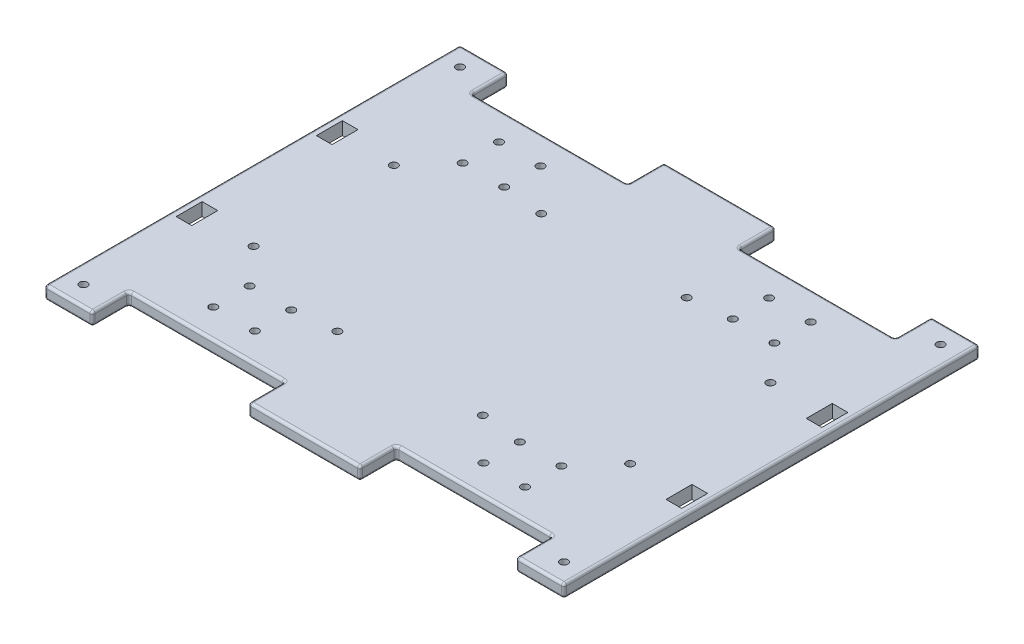
SolidWorks part; units mm, degrees
ref_plane "Front Plane" through (0, 0, 0) normal (0, 0, 1) x (1, 0, 0)
ref_plane "Top Plane" through (0, 0, 0) normal (0, 1, 0) x (1, 0, 0)
ref_plane "Right Plane" through (0, 0, 0) normal (1, 0, 0) x (0, 0, -1)
sketch "Sketch2" plane through (0, 0, 0) normal (0, 1, 0) x (1, 0, 0)
  line L1 (-100, -80) -> (100, -80)
  line L2 (-100, -80) -> (-100, 80)
  line L3 (-100, 80) -> (100, 80)
  line L4 (100, -80) -> (100, 80)
  line L5 (-100, -80) -> (100, 80) construction
  line L6 (-100, 80) -> (100, -80) construction
  point P0 (0, 0)
  dimension "D1" = 200
  dimension "D2" = 160
extrude "Boss-Extrude1" add sketch "Sketch2" along normal blind 5
sketch "Sketch3" plane through (0, 5, 0) normal (0, 1, 0) x (1, 0, 0)
  line L0 (100, -80) -> (100, 80) construction
  line L1 (100, 80) -> (-100, 80) construction
  circle A0 centre (92.5, 72.5) radius 1.5
  dimension "D1" = 3
  dimension "D3" = 7.5
  dimension "D2" = 7.5
extrude "Cut-Extrude1" cut sketch "Sketch3" against normal through all
mirror "Mirror1" about plane through (0, 0, 0) normal (1, 0, 0) of "Cut-Extrude1"
mirror "Mirror2" about plane through (0, 0, 0) normal (0, 0, 1) of "Mirror1", "Cut-Extrude1"
sketch "Sketch4" plane through (0, 5, 0) normal (0, 1, 0) x (1, 0, 0)
  line L0 (-100, 80) -> (-100, -80) construction
  line L1 (-52, -65.6362) -> (-52, -30.3638) construction
  line L2 (-36.7421, -48) -> (-67.2579, -48) construction
  line L3 (-100, -80) -> (100, -80) construction
  circle A0 centre (-60, -55) radius 1.5
  circle A1 centre (-60, -41) radius 1.5
  circle A2 centre (-44, -55) radius 1.5
  circle A3 centre (-44, -41) radius 1.5
  point P11 (-52, -48)
  dimension "D1" = 3
  dimension "D2" = 40
  dimension "D3" = 25
  dimension "D6" = 16
  dimension "D7" = 14
extrude "Cut-Extrude2" cut sketch "Sketch4" against normal through all
mirror "Mirror3" about plane through (0, 0, 0) normal (1, 0, 0) of "Cut-Extrude2"
mirror "Mirror4" about plane through (0, 0, 0) normal (0, 0, 1) of "Mirror3", "Cut-Extrude2"
sketch "Sketch6" plane through (0, 5, 0) normal (0, 1, 0) x (1, 0, 0)
  line L0 (-21.5, -80) -> (-21.5, -66)
  line L1 (-51.5, -36) -> (-51.5, -89.4353) construction
  line L2 (-81.5, -80) -> (-81.5, -66)
  line L3 (-21.5, -66) -> (-81.5, -66)
  line L7 (-100, -80) -> (100, -80) construction
  circle A0 centre (-44, -41) radius 1.5 construction
  point P8 (-71.5, -55.057)
  dimension "D4" = 14
  dimension "D3" = 30
  dimension "D1" = 30
  dimension "D2" = 7.5
extrude "Cut-Extrude4" cut sketch "Sketch6" against normal through all and the other way through all flip side to cut
mirror "Mirror8" about plane through (0, 0, 0) normal (0, 0, 1) of "Cut-Extrude4"
mirror "Mirror9" about plane through (0, 0, 0) normal (1, 0, 0) of "Mirror8", "Cut-Extrude4"
sketch "Sketch9" plane through (0, 0, 0) normal (0, -1, 0) x (-1, 0, 0)
  line L0 (0, 80) -> (0, -80) construction
  line L1 (21.5, -80) -> (-21.5, -80) construction
  line L2 (-100, 0) -> (100, 0) construction
  line L3 (100, 80) -> (100, -80) construction
  circle A0 centre (28, -39.25) radius 1.5
  point P6 (0, 0)
  point P12 (0, 0)
  dimension "D1" = 3
  dimension "D2" = 39.25
  dimension "D3" = 28
extrude "Cut-Extrude5" cut sketch "Sketch9" against normal through all
mirror "Mirror10" about plane through (0, 0, 0) normal (0, 0, 1) of "Cut-Extrude5"
mirror "Mirror11" about plane through (0, 0, 0) normal (1, 0, 0) of "Mirror10", "Cut-Extrude5"
sketch "Sketch10" plane through (0, 5, 0) normal (0, 1, 0) x (1, 0, 0)
  line L0 (-98, -19) -> (-66, -19) construction
  line L1 (-98, -19) -> (-98, -35) construction
  line L2 (-98, -35) -> (-66, -35) construction
  line L3 (-66, -35) -> (-66, -19) construction
  line L4 (-100, 80) -> (-100, -80) construction
  line L5 (-100, -80) -> (-81.5, -80) construction
  line L6 (-98, -27) -> (-66, -27) construction
  line L7 (-91.3, -32) -> (-97.3, -32)
  line L8 (-91.3, -32) -> (-91.3, -22)
  line L9 (-91.3, -22) -> (-97.3, -22)
  line L10 (-97.3, -32) -> (-97.3, -22)
  line L11 (-91.3, -32) -> (-97.3, -22) construction
  line L12 (-91.3, -22) -> (-97.3, -32) construction
  circle A0 centre (-72.5, -27) radius 1.5
  point P4 (-94.3, -27)
  point P17 (-86.3323, -27)
  point P18 (-69.5, -27)
  dimension "D5" = 3
  dimension "D1" = 16
  dimension "D2" = 32
  dimension "D3" = 2
  dimension "D4" = 45
  dimension "D6" = 6.5
  dimension "D7" = 10
  dimension "D8" = 6
  dimension "D9" = 25.3
extrude "Cut-Extrude6" cut sketch "Sketch10" against normal through all
mirror "Mirror12" about plane through (0, 0, 0) normal (0, 0, 1) of "Cut-Extrude6"
mirror "Mirror13" about plane through (0, 0, 0) normal (1, 0, 0) of "Mirror12", "Cut-Extrude6"
fillet "Fillet3" radius 1 60 edges at (100, 5, 0) (100, 0, 0) (90.75, 5, 80) (100, 2.5, 80) (90.75, 0, 80) (81.5, 0, 73) (81.5, 5, 73) (81.5, 2.5, 80) (51.5, 0, 66) (51.5, 5, 66) (81.5, 2.5, 66) (21.5, 0, 73) (21.5, 5, 73) (21.5, 2.5, 66) (0, 0, 80) (0, 5, 80) (21.5, 2.5, 80) (-21.5, 2.5, 80) (-21.5, 0, 73) (-21.5, 5, 73) (-21.5, 2.5, 66) (-51.5, 0, 66) (-51.5, 5, 66) (-81.5, 2.5, 66) (-81.5, 0, 73) (-81.5, 5, 73) (-90.75, 5, 80) (-81.5, 2.5, 80) (-90.75, 0, 80) (-100, 5, 0) (-100, 2.5, 80) (-100, 0, 0) (100, 2.5, -80) (90.75, 5, -80) (90.75, 0, -80) (81.5, 0, -73) (81.5, 2.5, -80) (81.5, 5, -73) (-81.5, 0, -73) (-81.5, 5, -73) (-90.75, 5, -80) (-100, 2.5, -80) (-90.75, 0, -80) (-81.5, 2.5, -80) (-51.5, 0, -66) (-51.5, 5, -66) (-81.5, 2.5, -66) (-21.5, 0, -73) (-21.5, 5, -73) (-21.5, 2.5, -66) (-21.5, 2.5, -80) (0, 0, -80) (0, 5, -80) (21.5, 2.5, -80) (21.5, 0, -73) (21.5, 5, -73) (21.5, 2.5, -66) (51.5, 0, -66) (81.5, 2.5, -66) (51.5, 5, -66)
